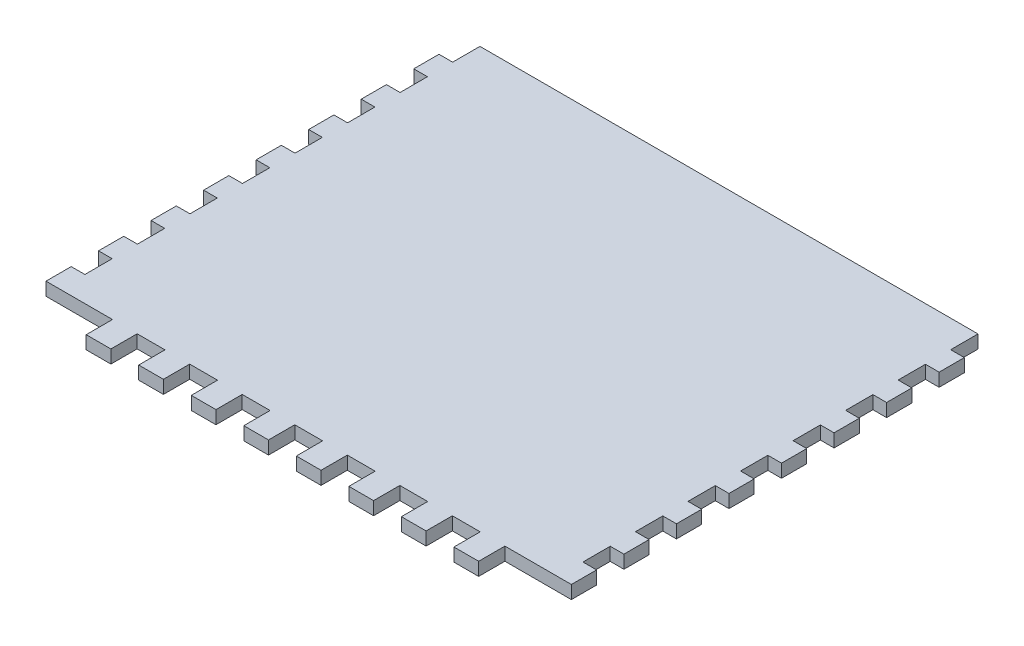
SolidWorks part; units mm, degrees
ref_plane "Front Plane" through (0, 0, 0) normal (0, 0, 1) x (1, 0, 0)
ref_plane "Top Plane" through (0, 0, 0) normal (0, 1, 0) x (1, 0, 0)
ref_plane "Right Plane" through (0, 0, 0) normal (1, 0, 0) x (0, 0, -1)
sketch "Sketch1" plane through (0, 0, 0) normal (0, 1, 0) x (1, 0, 0)
  line L1 (-63.5, -53.975) -> (63.5, -53.975)
  line L2 (-63.5, -53.975) -> (-63.5, 53.975)
  line L3 (-63.5, 53.975) -> (63.5, 53.975)
  line L4 (63.5, -53.975) -> (63.5, 53.975)
  line L5 (-63.5, -53.975) -> (63.5, 53.975) construction
  line L6 (-63.5, 53.975) -> (63.5, -53.975) construction
  point P0 (0, 0)
  dimension "D1" = 127
  dimension "D2" = 107.95
extrude "Boss-Extrude1" add sketch "Sketch1" along normal blind 3.175
sketch "Sketch2" plane through (0, 0, 0) normal (0, -1, 0) x (1, 0, 0)
  line L0 (-34.7345, 47.625) -> (-41.4655, 47.625)
  line L5 (63.5, 53.975) -> (63.5, -53.975) construction
  line L34 (0, 0) -> (0, -14.8721) construction
  line L39 (63.5, 41.529) -> (60.198, 41.529)
  line L41 (63.5, 54.229) -> (63.5, 47.625)
  line L42 (63.5, 47.625) -> (60.198, 47.625)
  line L44 (63.5, 41.529) -> (63.5, 34.925)
  line L45 (63.5, 34.925) -> (60.198, 34.925)
  line L46 (60.198, 41.529) -> (60.198, 34.925)
  line L47 (63.5, 28.829) -> (60.198, 28.829)
  line L48 (63.5, 28.829) -> (63.5, 22.225)
  line L49 (63.5, 22.225) -> (60.198, 22.225)
  line L50 (60.198, 28.829) -> (60.198, 22.225)
  line L51 (63.5, 16.129) -> (60.198, 16.129)
  line L52 (63.5, 16.129) -> (63.5, 9.525)
  line L53 (63.5, 9.525) -> (60.198, 9.525)
  line L54 (60.198, 16.129) -> (60.198, 9.525)
  line L55 (63.5, 3.429) -> (60.198, 3.429)
  line L56 (63.5, 3.429) -> (63.5, -3.175)
  line L57 (63.5, -3.175) -> (60.198, -3.175)
  line L58 (60.198, 3.429) -> (60.198, -3.175)
  line L59 (63.5, -9.271) -> (60.198, -9.271)
  line L60 (63.5, -9.271) -> (63.5, -15.875)
  line L61 (63.5, -15.875) -> (60.198, -15.875)
  line L62 (60.198, -9.271) -> (60.198, -15.875)
  line L63 (63.5, -21.971) -> (60.198, -21.971)
  line L64 (63.5, -21.971) -> (63.5, -28.575)
  line L65 (63.5, -28.575) -> (60.198, -28.575)
  line L66 (60.198, -21.971) -> (60.198, -28.575)
  line L67 (63.5, -34.671) -> (60.198, -34.671)
  line L68 (63.5, -34.671) -> (63.5, -41.275)
  line L69 (63.5, -41.275) -> (60.198, -41.275)
  line L70 (60.198, -34.671) -> (60.198, -41.275)
  line L71 (-60.198, -34.671) -> (-60.198, -41.275)
  line L72 (-63.5, -41.275) -> (-60.198, -41.275)
  line L73 (-63.5, -34.671) -> (-63.5, -41.275)
  line L74 (-63.5, -34.671) -> (-60.198, -34.671)
  line L75 (-60.198, -21.971) -> (-60.198, -28.575)
  line L76 (-63.5, -28.575) -> (-60.198, -28.575)
  line L77 (-63.5, -21.971) -> (-63.5, -28.575)
  line L78 (-63.5, -21.971) -> (-60.198, -21.971)
  line L79 (-60.198, -9.271) -> (-60.198, -15.875)
  line L80 (-63.5, -15.875) -> (-60.198, -15.875)
  line L81 (-63.5, -9.271) -> (-63.5, -15.875)
  line L82 (-63.5, -9.271) -> (-60.198, -9.271)
  line L83 (-60.198, 3.429) -> (-60.198, -3.175)
  line L84 (-63.5, -3.175) -> (-60.198, -3.175)
  line L85 (-63.5, 3.429) -> (-63.5, -3.175)
  line L86 (-63.5, 3.429) -> (-60.198, 3.429)
  line L87 (-60.198, 16.129) -> (-60.198, 9.525)
  line L88 (-63.5, 9.525) -> (-60.198, 9.525)
  line L89 (-63.5, 16.129) -> (-63.5, 9.525)
  line L90 (-63.5, 16.129) -> (-60.198, 16.129)
  line L91 (-60.198, 28.829) -> (-60.198, 22.225)
  line L92 (-63.5, 22.225) -> (-60.198, 22.225)
  line L93 (-63.5, 28.829) -> (-63.5, 22.225)
  line L94 (-63.5, 28.829) -> (-60.198, 28.829)
  line L95 (-60.198, 41.529) -> (-60.198, 34.925)
  line L96 (-63.5, 34.925) -> (-60.198, 34.925)
  line L97 (-63.5, 41.529) -> (-63.5, 34.925)
  line L99 (-63.5, 47.625) -> (-60.198, 47.625)
  line L100 (-63.5, 54.229) -> (-63.5, 47.625)
  line L102 (-63.5, 41.529) -> (-60.198, 41.529)
  line L103 (60.198, 47.625) -> (47.4345, 47.625)
  line L104 (34.7345, 47.625) -> (34.7345, 54.229)
  line L106 (34.7345, 54.229) -> (28.7655, 54.229)
  line L107 (28.7655, 54.229) -> (28.7655, 47.625)
  line L108 (28.7655, 47.625) -> (22.0345, 47.625)
  line L109 (22.0345, 47.625) -> (22.0345, 54.229)
  line L110 (22.0345, 54.229) -> (16.0655, 54.229)
  line L111 (16.0655, 54.229) -> (16.0655, 47.625)
  line L112 (16.0655, 47.625) -> (9.3345, 47.625)
  line L113 (9.3345, 47.625) -> (9.3345, 54.229)
  line L114 (9.3345, 54.229) -> (3.3655, 54.229)
  line L115 (3.3655, 54.229) -> (3.3655, 47.625)
  line L116 (3.3655, 47.625) -> (-3.3655, 47.625)
  line L117 (-3.3655, 47.625) -> (-3.3655, 54.229)
  line L118 (-3.3655, 54.229) -> (-9.3345, 54.229)
  line L119 (-9.3345, 54.229) -> (-9.3345, 47.625)
  line L120 (-9.3345, 47.625) -> (-16.0655, 47.625)
  line L121 (-16.0655, 47.625) -> (-16.0655, 54.229)
  line L122 (-16.0655, 54.229) -> (-22.0345, 54.229)
  line L123 (-22.0345, 54.229) -> (-22.0345, 47.625)
  line L124 (-22.0345, 47.625) -> (-28.7655, 47.625)
  line L125 (-28.7655, 47.625) -> (-28.7655, 54.229)
  line L126 (-28.7655, 54.229) -> (-34.7345, 54.229)
  line L127 (-34.7345, 54.229) -> (-34.7345, 47.625)
  line L137 (-63.5, 54.229) -> (-63.5, 63.0316)
  line L138 (63.5, -53.975) -> (-63.5, -53.975) construction
  line L139 (-63.5, 63.0316) -> (63.5, 63.0316)
  line L140 (63.5, 63.0316) -> (63.5, 54.229)
  line L141 (63.5, -47.371) -> (63.5, -53.975)
  line L142 (63.5, -53.975) -> (60.198, -53.975)
  line L143 (60.198, -53.975) -> (60.198, -47.371)
  line L144 (60.198, -47.371) -> (63.5, -47.371)
  line L145 (-60.198, -47.371) -> (-63.5, -47.371)
  line L146 (-60.198, -53.975) -> (-60.198, -47.371)
  line L147 (-63.5, -53.975) -> (-60.198, -53.975)
  line L148 (-63.5, -47.371) -> (-63.5, -53.975)
  line L149 (-63.5, -53.975) -> (-63.5, 53.975) construction
  line L150 (63.5, 53.975) -> (63.5, -53.975) construction
  line L151 (41.4655, 47.625) -> (41.4655, 54.229)
  line L152 (41.4655, 54.229) -> (47.4345, 54.229)
  line L153 (47.4345, 54.229) -> (47.4345, 47.625)
  line L154 (-41.4655, 47.625) -> (-41.4655, 54.229)
  line L155 (-41.4655, 54.229) -> (-47.4345, 54.229)
  line L156 (-47.4345, 54.229) -> (-47.4345, 47.625)
  line L157 (-47.4345, 47.625) -> (-60.198, 47.625)
  line L158 (41.4655, 47.625) -> (34.7345, 47.625)
  point P3 (0, 47.625)
  dimension "D2" = 6.604
  dimension "D3" = 5.969
  dimension "D6" = 6.731
  dimension "D8" = 3.302
  dimension "D9" = 9
extrude "Cut-Extrude1" cut sketch "Sketch2" against normal through all
